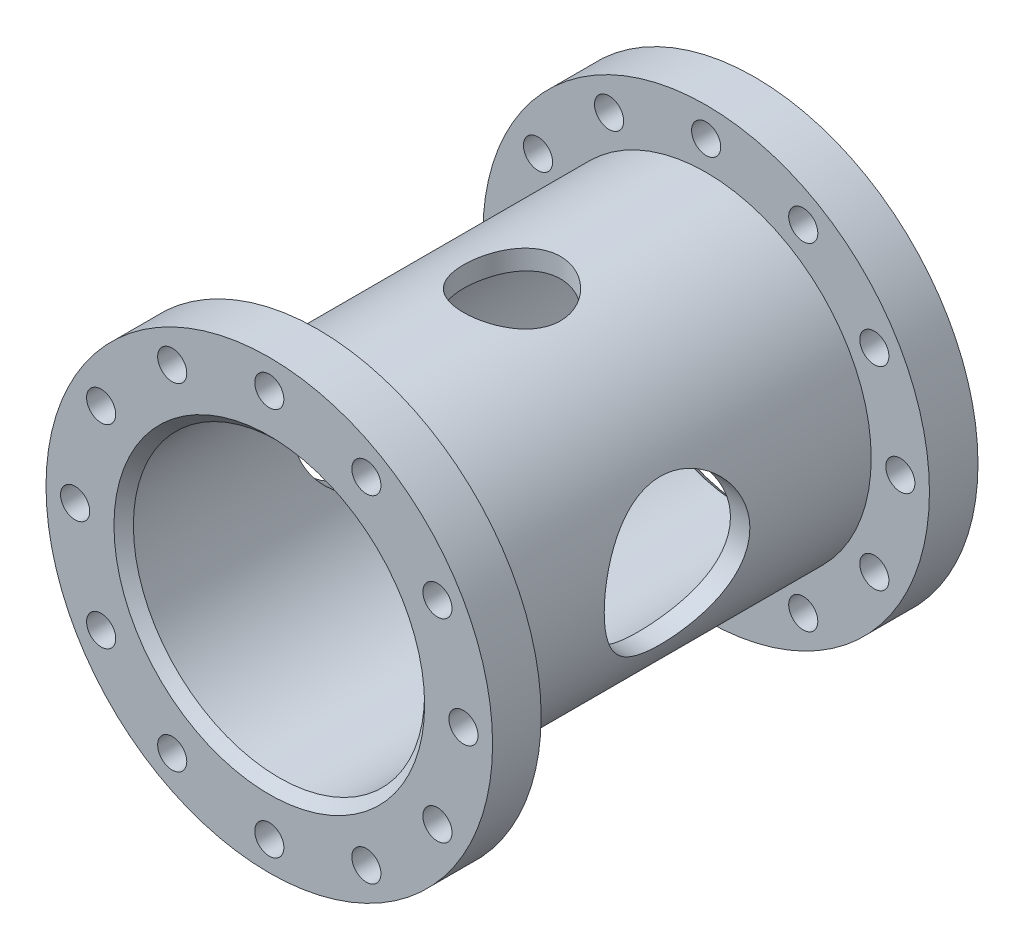
SolidWorks part; units mm, degrees
material "AISI 1020"
ref_plane "Front Plane" through (0, 0, 0) normal (0, 0, 1) x (1, 0, 0)
ref_plane "Top Plane" through (0, 0, 0) normal (0, 1, 0) x (1, 0, 0)
ref_plane "Right Plane" through (0, 0, 0) normal (1, 0, 0) x (0, 0, -1)
sketch "Sketch1" plane through (0, 0, 0) normal (0, 0, 1) x (1, 0, 0)
  circle A0 centre (0, 0) radius 75
  circle A1 centre (0, 0) radius 85
  dimension "D1" = 10
  dimension "D2" = 150
extrude "Boss-Extrude1" add sketch "Sketch1" along normal blind 100
sketch "Sketch2" plane through (0, 0, 100) normal (0, 0, 1) x (1, 0, 0)
  circle A0 centre (0, 0) radius 115
  circle A1 centre (0, 0) radius 75 construction
  circle A2 centre (0, 0) radius 75
  dimension "D1" = 40
extrude "Boss-Extrude2" add sketch "Sketch2" along normal blind 25
hole_wizard "Ø15.0 (15) Diameter Hole1" positions "Sketch3" profile "Sketch4" hole size "Ø15.0" standard "ANSI Metric" end condition up to next
sketch "Sketch3" plane through (0, 0, 125) normal (0, 0, 1) x (1, 0, 0)
  line L0 (0, 0) -> (0, 100) construction
  circle A1 centre (0, 0) radius 115 construction
  point P0 (0, 100)
  dimension "D1" = 15
sketch "Sketch4" plane through (0, 100, 125) normal (1, 0, 0) x (0, -1, 0)
  line L0 (0, 0) -> (0, 25.001)
  line L1 (0, 25.001) -> (7.5, 25.001)
  line L2 (7.5, 25.001) -> (7.5, 0)
  line L5 (7.5, 0) -> (0, 0)
  line L11 (0, -6.35) -> (0, 107.95) construction
  dimension "Thru Hole Dia." = 15
  dimension "Thru Hole Depth" = 25.001
pattern_circular "CirPattern1" count 12 over 360 about axis through (0, 0, 0) along (0, 0, 1) of "Ø15.0 (15) Diameter Hole1"
sketch "Sketch6" [suppressed] plane through (0, 0, 125) normal (0, 0, 1) x (1, 0, 0)
  circle A0 centre (0, 0) radius 75 construction
  circle A1 centre (0, 0) radius 115
  circle A2 centre (0, 0) radius 115
  circle A3 centre (0, 0) radius 75
  dimension "D1" = 0
extrude "FACE-MATERIAL" [suppressed] add sketch "Sketch6" along normal blind 5
chamfer "Chamfer1" distance 5 angle 45 1 edges at (75, 0, 125)
mirror "Mirror1" about plane through (0, 0, 0) normal (0, 0, 1) of bodies 104
sketch "Sketch5" plane through (0, 0, 0) normal (1, 0, 0) x (0, 0, -1)
  circle A0 centre (0, 0) radius 37.5
  dimension "D1" = 75
extrude "Cut-Extrude1" cut sketch "Sketch5" against normal through all both and the other way through all
sketch "Sketch7" plane through (0, 0, 0) normal (0, 1, 0) x (1, 0, 0)
  circle A0 centre (0, 0) radius 25
  dimension "D1" = 50
extrude "Cut-Extrude2" cut sketch "Sketch7" against normal through all both and the other way through all
equation "\"A\"= 100"
equation "\"B\"= 100"
equation "\"C\"= 100"
equation "\"D\"= 100"
equation "\"E\"= 100"
